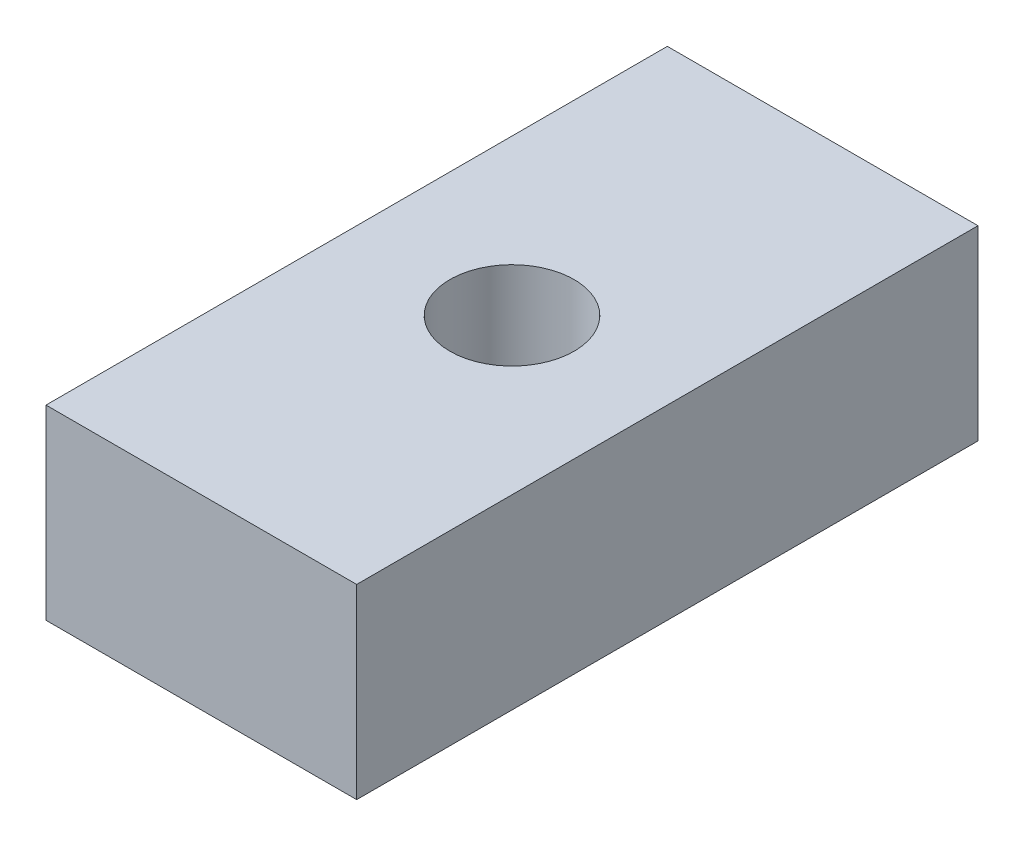
SolidWorks part; units mm, degrees
ref_plane "Plan de face" through (0, 0, 0) normal (0, 0, 1) x (1, 0, 0)
ref_plane "Plan de dessus" through (0, 0, 0) normal (0, 1, 0) x (1, 0, 0)
ref_plane "Plan de droite" through (0, 0, 0) normal (1, 0, 0) x (0, 0, -1)
sketch "Esquisse1" plane through (0, 0, 0) normal (0, 1, 0) x (1, 0, 0)
  line L1 (0, 0) -> (5, 0)
  line L2 (0, 0) -> (0, -10)
  line L3 (0, -10) -> (5, -10)
  line L4 (5, 0) -> (5, -10)
  dimension "D1" = 10
  dimension "D2" = 5
extrude "Boss.-Extru.1" add sketch "Esquisse1" along normal blind 3
sketch "Esquisse2" plane through (0, 3, 0) normal (0, 1, 0) x (1, 0, 0)
  line L0 (0, -10) -> (5, -10) construction
  line L1 (5, -10) -> (5, 0) construction
  circle A0 centre (2.5, -5) radius 1
  dimension "D1" = 2
  dimension "D2" = 5
  dimension "D3" = 2.5
extrude "Enlèv. mat.-Extru.1" cut sketch "Esquisse2" against normal through all
